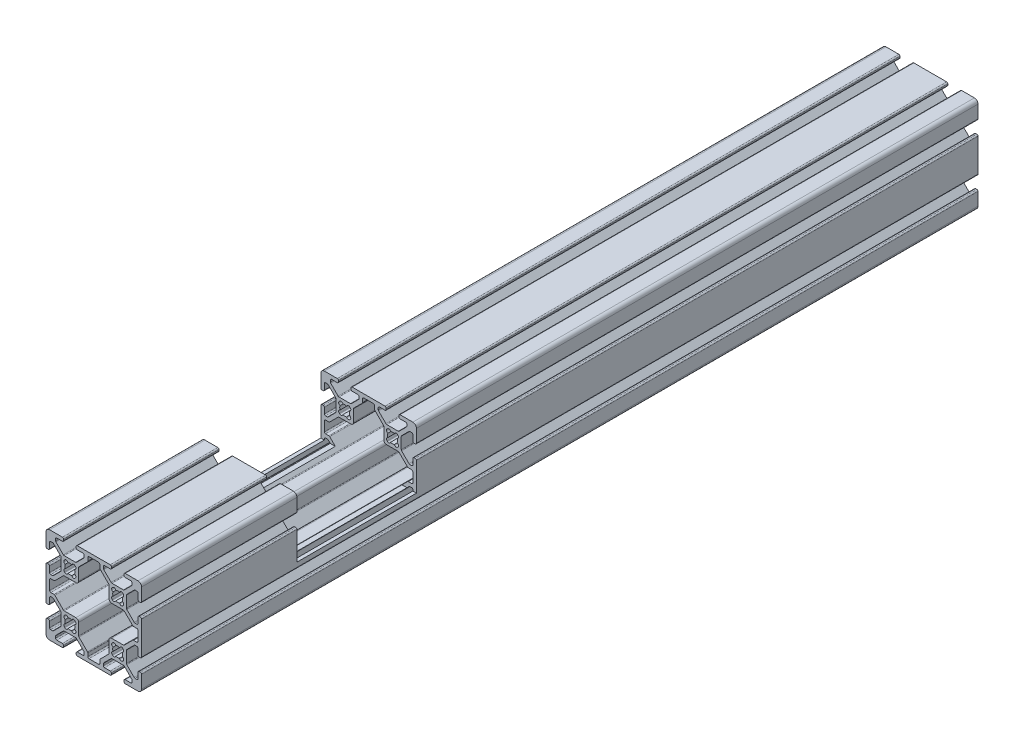
SolidWorks part; units mm, degrees
material "6105-T5 Aluminum"
ref_plane "Front Plane" through (0, 0, 0) normal (0, 0, 1) x (1, 0, 0)
ref_plane "Top Plane" through (0, 0, 0) normal (0, 1, 0) x (1, 0, 0)
ref_plane "Right Plane" through (0, 0, 0) normal (1, 0, 0) x (0, 0, -1)
sketch "Sketch1" plane through (0, 0, 0) normal (0, 0, 1) x (1, 0, 0)
  line L0 (-2.1249, 17.6955) -> (-2.3045, 17.8751)
  line L1 (-2.3045, 22.1249) -> (-2.1249, 22.3045)
  line L2 (2.1249, 22.3045) -> (2.3045, 22.1249)
  line L3 (2.3045, 17.8751) -> (2.1249, 17.6955)
  line L4 (-22.1249, 17.6955) -> (-22.3045, 17.8751)
  line L5 (-22.3045, 22.1249) -> (-22.1249, 22.3045)
  line L6 (-17.8751, 22.3045) -> (-17.6955, 22.1249)
  line L7 (-17.6955, 17.8751) -> (-17.8751, 17.6955)
  line L8 (-2.1249, -2.3045) -> (-2.3045, -2.1249)
  line L9 (-2.3045, 2.1249) -> (-2.1249, 2.3045)
  line L10 (2.1249, 2.3045) -> (2.3045, 2.1249)
  line L11 (2.3045, -2.1249) -> (2.1249, -2.3045)
  line L12 (-12.505, -7.992) -> (-12.505, -6.6448)
  line L13 (-12.6538, -6.2856) -> (-16.1962, -2.7431)
  line L14 (-16.345, -2.3839) -> (-16.345, 2.512)
  line L15 (-17.488, 3.655) -> (-22.3839, 3.655)
  line L16 (-22.7431, 3.8038) -> (-26.2856, 7.3462)
  line L17 (-26.6448, 7.495) -> (-27.992, 7.495)
  line L18 (-28.5, 8.003) -> (-28.5, 11.997)
  line L19 (-27.992, 12.505) -> (-26.6448, 12.505)
  line L20 (-26.2856, 12.6538) -> (-22.7431, 16.1962)
  line L21 (-22.3839, 16.345) -> (-17.488, 16.345)
  line L22 (-16.345, 17.488) -> (-16.345, 22.3839)
  line L23 (-16.1962, 22.7431) -> (-12.6538, 26.2856)
  line L24 (-12.505, 26.6448) -> (-12.505, 27.992)
  line L25 (-11.997, 28.5) -> (-8.003, 28.5)
  line L26 (-7.495, 27.992) -> (-7.495, 26.6448)
  line L27 (-7.3462, 26.2856) -> (-3.8038, 22.7431)
  line L28 (-3.655, 22.3839) -> (-3.655, 17.488)
  line L29 (-2.512, 16.345) -> (2.3839, 16.345)
  line L30 (2.7431, 16.1962) -> (6.2856, 12.6538)
  line L31 (6.6448, 12.505) -> (7.992, 12.505)
  line L32 (8.5, 11.997) -> (8.5, 8.003)
  line L33 (7.992, 7.495) -> (6.6448, 7.495)
  line L34 (6.2856, 7.3462) -> (2.7431, 3.8038)
  line L35 (2.3839, 3.655) -> (-2.512, 3.655)
  line L36 (-3.655, 2.512) -> (-3.655, -2.3839)
  line L37 (-3.8038, -2.7431) -> (-7.3462, -6.2856)
  line L38 (-7.495, -6.6448) -> (-7.495, -7.992)
  line L39 (-8.003, -8.5) -> (-11.997, -8.5)
  line L40 (-22.1249, -2.3045) -> (-22.3045, -2.1249)
  line L41 (-22.3045, 2.1249) -> (-22.1249, 2.3045)
  line L42 (-17.8751, 2.3045) -> (-17.6955, 2.1249)
  line L43 (-17.6955, -2.1249) -> (-17.8751, -2.3045)
  line L44 (-22.3839, -3.655) -> (-17.6161, -3.655)
  line L45 (-17.2569, -3.8038) -> (-14.1538, -6.9069)
  line L46 (-14.005, -7.2661) -> (-14.005, -7.992)
  line L47 (-14.513, -8.5) -> (-16.862, -8.5)
  line L48 (-17.37, -9.008) -> (-17.37, -9.492)
  line L49 (-16.862, -10) -> (-3.138, -10)
  line L50 (-2.63, -9.492) -> (-2.63, -9.008)
  line L51 (-3.138, -8.5) -> (-5.487, -8.5)
  line L52 (-5.995, -7.992) -> (-5.995, -7.2661)
  line L53 (-5.8462, -6.9069) -> (-2.7431, -3.8038)
  line L54 (-2.3839, -3.655) -> (2.3839, -3.655)
  line L55 (2.7431, -3.8038) -> (5.8462, -6.9069)
  line L56 (5.995, -7.2661) -> (5.995, -7.992)
  line L57 (5.487, -8.5) -> (3.138, -8.5)
  line L58 (2.63, -9.008) -> (2.63, -9.492)
  line L59 (3.138, -10) -> (8.5, -10)
  line L60 (10, -8.5) -> (10, -3.138)
  line L61 (9.492, -2.63) -> (9.008, -2.63)
  line L62 (8.5, -3.138) -> (8.5, -5.487)
  line L63 (7.992, -5.995) -> (7.2661, -5.995)
  line L64 (6.9069, -5.8462) -> (3.8038, -2.7431)
  line L65 (3.655, -2.3839) -> (3.655, 2.3839)
  line L66 (3.8038, 2.7431) -> (6.9069, 5.8462)
  line L67 (7.2661, 5.995) -> (7.992, 5.995)
  line L68 (8.5, 5.487) -> (8.5, 3.138)
  line L69 (9.008, 2.63) -> (9.492, 2.63)
  line L70 (10, 3.138) -> (10, 16.862)
  line L71 (9.492, 17.37) -> (9.008, 17.37)
  line L72 (8.5, 16.862) -> (8.5, 14.513)
  line L73 (7.992, 14.005) -> (7.2661, 14.005)
  line L74 (6.9069, 14.1538) -> (3.8038, 17.2569)
  line L75 (3.655, 17.6161) -> (3.655, 22.3839)
  line L76 (3.8038, 22.7431) -> (6.9069, 25.8462)
  line L77 (7.2661, 25.995) -> (7.992, 25.995)
  line L78 (8.5, 25.487) -> (8.5, 23.138)
  line L79 (9.008, 22.63) -> (9.492, 22.63)
  line L80 (10, 23.138) -> (10, 28.5)
  line L81 (8.5, 30) -> (3.138, 30)
  line L82 (2.63, 29.492) -> (2.63, 29.008)
  line L83 (3.138, 28.5) -> (5.487, 28.5)
  line L84 (5.995, 27.992) -> (5.995, 27.2661)
  line L85 (5.8462, 26.9069) -> (2.7431, 23.8038)
  line L86 (2.3839, 23.655) -> (-2.3839, 23.655)
  line L87 (-2.7431, 23.8038) -> (-5.8462, 26.9069)
  line L88 (-5.995, 27.2661) -> (-5.995, 27.992)
  line L89 (-5.487, 28.5) -> (-3.138, 28.5)
  line L90 (-2.63, 29.008) -> (-2.63, 29.492)
  line L91 (-3.138, 30) -> (-16.862, 30)
  line L92 (-17.37, 29.492) -> (-17.37, 29.008)
  line L93 (-16.862, 28.5) -> (-14.513, 28.5)
  line L94 (-14.005, 27.992) -> (-14.005, 27.2661)
  line L95 (-14.1538, 26.9069) -> (-17.2569, 23.8038)
  line L96 (-17.6161, 23.655) -> (-22.3839, 23.655)
  line L97 (-22.7431, 23.8038) -> (-25.8462, 26.9069)
  line L98 (-25.995, 27.2661) -> (-25.995, 27.992)
  line L99 (-25.487, 28.5) -> (-23.138, 28.5)
  line L100 (-22.63, 29.008) -> (-22.63, 29.492)
  line L101 (-23.138, 30) -> (-28.5, 30)
  line L102 (-30, 28.5) -> (-30, 23.138)
  line L103 (-29.492, 22.63) -> (-29.008, 22.63)
  line L104 (-28.5, 23.138) -> (-28.5, 25.487)
  line L105 (-27.992, 25.995) -> (-27.2661, 25.995)
  line L106 (-26.9069, 25.8462) -> (-23.8038, 22.7431)
  line L107 (-23.655, 22.3839) -> (-23.655, 17.6161)
  line L108 (-23.8038, 17.2569) -> (-26.9069, 14.1538)
  line L109 (-27.2661, 14.005) -> (-27.992, 14.005)
  line L110 (-28.5, 14.513) -> (-28.5, 16.862)
  line L111 (-29.008, 17.37) -> (-29.492, 17.37)
  line L112 (-30, 16.862) -> (-30, 3.138)
  line L113 (-29.492, 2.63) -> (-29.008, 2.63)
  line L114 (-28.5, 3.138) -> (-28.5, 5.487)
  line L115 (-27.992, 5.995) -> (-27.2661, 5.995)
  line L116 (-26.9069, 5.8462) -> (-23.8038, 2.7431)
  line L117 (-23.655, 2.3839) -> (-23.655, -2.3839)
  line L118 (-23.8038, -2.7431) -> (-26.9069, -5.8462)
  line L119 (-27.2661, -5.995) -> (-27.992, -5.995)
  line L120 (-28.5, -5.487) -> (-28.5, -3.138)
  line L121 (-29.008, -2.63) -> (-29.492, -2.63)
  line L122 (-30, -3.138) -> (-30, -8.5)
  line L123 (-28.5, -10) -> (-23.138, -10)
  line L124 (-22.63, -9.492) -> (-22.63, -9.008)
  line L125 (-23.138, -8.5) -> (-25.487, -8.5)
  line L126 (-25.995, -7.992) -> (-25.995, -7.2661)
  line L127 (-25.8462, -6.9069) -> (-22.7431, -3.8038)
  arc A0 (-1.9351, 19.196) -> (-2.3045, 17.8751) centre (-1.748, 18.4316) ccw
  arc A1 (-1.9351, 20.804) -> (-1.9351, 19.196) centre (0, 20) ccw
  arc A2 (-2.3045, 22.1249) -> (-1.9351, 20.804) centre (-1.748, 21.5684) ccw
  arc A3 (-0.804, 21.9351) -> (-2.1249, 22.3045) centre (-1.5684, 21.748) ccw
  arc A4 (0.804, 21.9351) -> (-0.804, 21.9351) centre (0, 20) ccw
  arc A5 (2.1249, 22.3045) -> (0.804, 21.9351) centre (1.5684, 21.748) ccw
  arc A6 (1.9351, 20.804) -> (2.3045, 22.1249) centre (1.748, 21.5684) ccw
  arc A7 (1.9351, 19.196) -> (1.9351, 20.804) centre (0, 20) ccw
  arc A8 (2.3045, 17.8751) -> (1.9351, 19.196) centre (1.748, 18.4316) ccw
  arc A9 (0.804, 18.0649) -> (2.1249, 17.6955) centre (1.5684, 18.252) ccw
  arc A10 (-0.804, 18.0649) -> (0.804, 18.0649) centre (0, 20) ccw
  arc A11 (-2.1249, 17.6955) -> (-0.804, 18.0649) centre (-1.5684, 18.252) ccw
  arc A12 (-21.9351, 19.196) -> (-22.3045, 17.8751) centre (-21.748, 18.4316) ccw
  arc A13 (-21.9351, 20.804) -> (-21.9351, 19.196) centre (-20, 20) ccw
  arc A14 (-22.3045, 22.1249) -> (-21.9351, 20.804) centre (-21.748, 21.5684) ccw
  arc A15 (-20.804, 21.9351) -> (-22.1249, 22.3045) centre (-21.5684, 21.748) ccw
  arc A16 (-19.196, 21.9351) -> (-20.804, 21.9351) centre (-20, 20) ccw
  arc A17 (-17.8751, 22.3045) -> (-19.196, 21.9351) centre (-18.4316, 21.748) ccw
  arc A18 (-18.0649, 20.804) -> (-17.6955, 22.1249) centre (-18.252, 21.5684) ccw
  arc A19 (-18.0649, 19.196) -> (-18.0649, 20.804) centre (-20, 20) ccw
  arc A20 (-17.6955, 17.8751) -> (-18.0649, 19.196) centre (-18.252, 18.4316) ccw
  arc A21 (-19.196, 18.0649) -> (-17.8751, 17.6955) centre (-18.4316, 18.252) ccw
  arc A22 (-20.804, 18.0649) -> (-19.196, 18.0649) centre (-20, 20) ccw
  arc A23 (-22.1249, 17.6955) -> (-20.804, 18.0649) centre (-21.5684, 18.252) ccw
  arc A24 (-1.9351, -0.804) -> (-2.3045, -2.1249) centre (-1.748, -1.5684) ccw
  arc A25 (-1.9351, 0.804) -> (-1.9351, -0.804) centre (0, 0) ccw
  arc A26 (-2.3045, 2.1249) -> (-1.9351, 0.804) centre (-1.748, 1.5684) ccw
  arc A27 (-0.804, 1.9351) -> (-2.1249, 2.3045) centre (-1.5684, 1.748) ccw
  arc A28 (0.804, 1.9351) -> (-0.804, 1.9351) centre (0, 0) ccw
  arc A29 (2.1249, 2.3045) -> (0.804, 1.9351) centre (1.5684, 1.748) ccw
  arc A30 (1.9351, 0.804) -> (2.3045, 2.1249) centre (1.748, 1.5684) ccw
  arc A31 (1.9351, -0.804) -> (1.9351, 0.804) centre (0, 0) ccw
  arc A32 (2.3045, -2.1249) -> (1.9351, -0.804) centre (1.748, -1.5684) ccw
  arc A33 (0.804, -1.9351) -> (2.1249, -2.3045) centre (1.5684, -1.748) ccw
  arc A34 (-0.804, -1.9351) -> (0.804, -1.9351) centre (0, 0) ccw
  arc A35 (-2.1249, -2.3045) -> (-0.804, -1.9351) centre (-1.5684, -1.748) ccw
  arc A36 (-12.505, -7.992) -> (-11.997, -8.5) centre (-11.997, -7.992) ccw
  arc A37 (-12.505, -6.6448) -> (-12.6538, -6.2856) centre (-13.013, -6.6448) ccw
  arc A38 (-16.345, -2.3839) -> (-16.1962, -2.7431) centre (-15.837, -2.3839) ccw
  arc A39 (-16.345, 2.512) -> (-17.488, 3.655) centre (-17.488, 2.512) ccw
  arc A40 (-22.7431, 3.8038) -> (-22.3839, 3.655) centre (-22.3839, 4.163) ccw
  arc A41 (-26.2856, 7.3462) -> (-26.6448, 7.495) centre (-26.6448, 6.987) ccw
  arc A42 (-28.5, 8.003) -> (-27.992, 7.495) centre (-27.992, 8.003) ccw
  arc A43 (-27.992, 12.505) -> (-28.5, 11.997) centre (-27.992, 11.997) ccw
  arc A44 (-26.6448, 12.505) -> (-26.2856, 12.6538) centre (-26.6448, 13.013) ccw
  arc A45 (-22.3839, 16.345) -> (-22.7431, 16.1962) centre (-22.3839, 15.837) ccw
  arc A46 (-17.488, 16.345) -> (-16.345, 17.488) centre (-17.488, 17.488) ccw
  arc A47 (-16.1962, 22.7431) -> (-16.345, 22.3839) centre (-15.837, 22.3839) ccw
  arc A48 (-12.6538, 26.2856) -> (-12.505, 26.6448) centre (-13.013, 26.6448) ccw
  arc A49 (-11.997, 28.5) -> (-12.505, 27.992) centre (-11.997, 27.992) ccw
  arc A50 (-7.495, 27.992) -> (-8.003, 28.5) centre (-8.003, 27.992) ccw
  arc A51 (-7.495, 26.6448) -> (-7.3462, 26.2856) centre (-6.987, 26.6448) ccw
  arc A52 (-3.655, 22.3839) -> (-3.8038, 22.7431) centre (-4.163, 22.3839) ccw
  arc A53 (-3.655, 17.488) -> (-2.512, 16.345) centre (-2.512, 17.488) ccw
  arc A54 (2.7431, 16.1962) -> (2.3839, 16.345) centre (2.3839, 15.837) ccw
  arc A55 (6.2856, 12.6538) -> (6.6448, 12.505) centre (6.6448, 13.013) ccw
  arc A56 (8.5, 11.997) -> (7.992, 12.505) centre (7.992, 11.997) ccw
  arc A57 (7.992, 7.495) -> (8.5, 8.003) centre (7.992, 8.003) ccw
  arc A58 (6.6448, 7.495) -> (6.2856, 7.3462) centre (6.6448, 6.987) ccw
  arc A59 (2.3839, 3.655) -> (2.7431, 3.8038) centre (2.3839, 4.163) ccw
  arc A60 (-2.512, 3.655) -> (-3.655, 2.512) centre (-2.512, 2.512) ccw
  arc A61 (-3.8038, -2.7431) -> (-3.655, -2.3839) centre (-4.163, -2.3839) ccw
  arc A62 (-7.3462, -6.2856) -> (-7.495, -6.6448) centre (-6.987, -6.6448) ccw
  arc A63 (-8.003, -8.5) -> (-7.495, -7.992) centre (-8.003, -7.992) ccw
  arc A64 (-21.9351, -0.804) -> (-22.3045, -2.1249) centre (-21.748, -1.5684) ccw
  arc A65 (-21.9351, 0.804) -> (-21.9351, -0.804) centre (-20, 0) ccw
  arc A66 (-22.3045, 2.1249) -> (-21.9351, 0.804) centre (-21.748, 1.5684) ccw
  arc A67 (-20.804, 1.9351) -> (-22.1249, 2.3045) centre (-21.5684, 1.748) ccw
  arc A68 (-19.196, 1.9351) -> (-20.804, 1.9351) centre (-20, 0) ccw
  arc A69 (-17.8751, 2.3045) -> (-19.196, 1.9351) centre (-18.4316, 1.748) ccw
  arc A70 (-18.0649, 0.804) -> (-17.6955, 2.1249) centre (-18.252, 1.5684) ccw
  arc A71 (-18.0649, -0.804) -> (-18.0649, 0.804) centre (-20, 0) ccw
  arc A72 (-17.6955, -2.1249) -> (-18.0649, -0.804) centre (-18.252, -1.5684) ccw
  arc A73 (-19.196, -1.9351) -> (-17.8751, -2.3045) centre (-18.4316, -1.748) ccw
  arc A74 (-20.804, -1.9351) -> (-19.196, -1.9351) centre (-20, 0) ccw
  arc A75 (-22.1249, -2.3045) -> (-20.804, -1.9351) centre (-21.5684, -1.748) ccw
  arc A76 (-22.3839, -3.655) -> (-22.7431, -3.8038) centre (-22.3839, -4.163) ccw
  arc A77 (-17.2569, -3.8038) -> (-17.6161, -3.655) centre (-17.6161, -4.163) ccw
  arc A78 (-14.005, -7.2661) -> (-14.1538, -6.9069) centre (-14.513, -7.2661) ccw
  arc A79 (-14.513, -8.5) -> (-14.005, -7.992) centre (-14.513, -7.992) ccw
  arc A80 (-16.862, -8.5) -> (-17.37, -9.008) centre (-16.862, -9.008) ccw
  arc A81 (-17.37, -9.492) -> (-16.862, -10) centre (-16.862, -9.492) ccw
  arc A82 (-3.138, -10) -> (-2.63, -9.492) centre (-3.138, -9.492) ccw
  arc A83 (-2.63, -9.008) -> (-3.138, -8.5) centre (-3.138, -9.008) ccw
  arc A84 (-5.995, -7.992) -> (-5.487, -8.5) centre (-5.487, -7.992) ccw
  arc A85 (-5.8462, -6.9069) -> (-5.995, -7.2661) centre (-5.487, -7.2661) ccw
  arc A86 (-2.3839, -3.655) -> (-2.7431, -3.8038) centre (-2.3839, -4.163) ccw
  arc A87 (2.7431, -3.8038) -> (2.3839, -3.655) centre (2.3839, -4.163) ccw
  arc A88 (5.995, -7.2661) -> (5.8462, -6.9069) centre (5.487, -7.2661) ccw
  arc A89 (5.487, -8.5) -> (5.995, -7.992) centre (5.487, -7.992) ccw
  arc A90 (3.138, -8.5) -> (2.63, -9.008) centre (3.138, -9.008) ccw
  arc A91 (2.63, -9.492) -> (3.138, -10) centre (3.138, -9.492) ccw
  arc A92 (8.5, -10) -> (10, -8.5) centre (8.5, -8.5) ccw
  arc A93 (10, -3.138) -> (9.492, -2.63) centre (9.492, -3.138) ccw
  arc A94 (9.008, -2.63) -> (8.5, -3.138) centre (9.008, -3.138) ccw
  arc A95 (7.992, -5.995) -> (8.5, -5.487) centre (7.992, -5.487) ccw
  arc A96 (6.9069, -5.8462) -> (7.2661, -5.995) centre (7.2661, -5.487) ccw
  arc A97 (3.655, -2.3839) -> (3.8038, -2.7431) centre (4.163, -2.3839) ccw
  arc A98 (3.8038, 2.7431) -> (3.655, 2.3839) centre (4.163, 2.3839) ccw
  arc A99 (7.2661, 5.995) -> (6.9069, 5.8462) centre (7.2661, 5.487) ccw
  arc A100 (8.5, 5.487) -> (7.992, 5.995) centre (7.992, 5.487) ccw
  arc A101 (8.5, 3.138) -> (9.008, 2.63) centre (9.008, 3.138) ccw
  arc A102 (9.492, 2.63) -> (10, 3.138) centre (9.492, 3.138) ccw
  arc A103 (10, 16.862) -> (9.492, 17.37) centre (9.492, 16.862) ccw
  arc A104 (9.008, 17.37) -> (8.5, 16.862) centre (9.008, 16.862) ccw
  arc A105 (7.992, 14.005) -> (8.5, 14.513) centre (7.992, 14.513) ccw
  arc A106 (6.9069, 14.1538) -> (7.2661, 14.005) centre (7.2661, 14.513) ccw
  arc A107 (3.655, 17.6161) -> (3.8038, 17.2569) centre (4.163, 17.6161) ccw
  arc A108 (3.8038, 22.7431) -> (3.655, 22.3839) centre (4.163, 22.3839) ccw
  arc A109 (7.2661, 25.995) -> (6.9069, 25.8462) centre (7.2661, 25.487) ccw
  arc A110 (8.5, 25.487) -> (7.992, 25.995) centre (7.992, 25.487) ccw
  arc A111 (8.5, 23.138) -> (9.008, 22.63) centre (9.008, 23.138) ccw
  arc A112 (9.492, 22.63) -> (10, 23.138) centre (9.492, 23.138) ccw
  arc A113 (10, 28.5) -> (8.5, 30) centre (8.5, 28.5) ccw
  arc A114 (3.138, 30) -> (2.63, 29.492) centre (3.138, 29.492) ccw
  arc A115 (2.63, 29.008) -> (3.138, 28.5) centre (3.138, 29.008) ccw
  arc A116 (5.995, 27.992) -> (5.487, 28.5) centre (5.487, 27.992) ccw
  arc A117 (5.8462, 26.9069) -> (5.995, 27.2661) centre (5.487, 27.2661) ccw
  arc A118 (2.3839, 23.655) -> (2.7431, 23.8038) centre (2.3839, 24.163) ccw
  arc A119 (-2.7431, 23.8038) -> (-2.3839, 23.655) centre (-2.3839, 24.163) ccw
  arc A120 (-5.995, 27.2661) -> (-5.8462, 26.9069) centre (-5.487, 27.2661) ccw
  arc A121 (-5.487, 28.5) -> (-5.995, 27.992) centre (-5.487, 27.992) ccw
  arc A122 (-3.138, 28.5) -> (-2.63, 29.008) centre (-3.138, 29.008) ccw
  arc A123 (-2.63, 29.492) -> (-3.138, 30) centre (-3.138, 29.492) ccw
  arc A124 (-16.862, 30) -> (-17.37, 29.492) centre (-16.862, 29.492) ccw
  arc A125 (-17.37, 29.008) -> (-16.862, 28.5) centre (-16.862, 29.008) ccw
  arc A126 (-14.005, 27.992) -> (-14.513, 28.5) centre (-14.513, 27.992) ccw
  arc A127 (-14.1538, 26.9069) -> (-14.005, 27.2661) centre (-14.513, 27.2661) ccw
  arc A128 (-17.6161, 23.655) -> (-17.2569, 23.8038) centre (-17.6161, 24.163) ccw
  arc A129 (-22.7431, 23.8038) -> (-22.3839, 23.655) centre (-22.3839, 24.163) ccw
  arc A130 (-25.995, 27.2661) -> (-25.8462, 26.9069) centre (-25.487, 27.2661) ccw
  arc A131 (-25.487, 28.5) -> (-25.995, 27.992) centre (-25.487, 27.992) ccw
  arc A132 (-23.138, 28.5) -> (-22.63, 29.008) centre (-23.138, 29.008) ccw
  arc A133 (-22.63, 29.492) -> (-23.138, 30) centre (-23.138, 29.492) ccw
  arc A134 (-28.5, 30) -> (-30, 28.5) centre (-28.5, 28.5) ccw
  arc A135 (-30, 23.138) -> (-29.492, 22.63) centre (-29.492, 23.138) ccw
  arc A136 (-29.008, 22.63) -> (-28.5, 23.138) centre (-29.008, 23.138) ccw
  arc A137 (-27.992, 25.995) -> (-28.5, 25.487) centre (-27.992, 25.487) ccw
  arc A138 (-26.9069, 25.8462) -> (-27.2661, 25.995) centre (-27.2661, 25.487) ccw
  arc A139 (-23.655, 22.3839) -> (-23.8038, 22.7431) centre (-24.163, 22.3839) ccw
  arc A140 (-23.8038, 17.2569) -> (-23.655, 17.6161) centre (-24.163, 17.6161) ccw
  arc A141 (-27.2661, 14.005) -> (-26.9069, 14.1538) centre (-27.2661, 14.513) ccw
  arc A142 (-28.5, 14.513) -> (-27.992, 14.005) centre (-27.992, 14.513) ccw
  arc A143 (-28.5, 16.862) -> (-29.008, 17.37) centre (-29.008, 16.862) ccw
  arc A144 (-29.492, 17.37) -> (-30, 16.862) centre (-29.492, 16.862) ccw
  arc A145 (-30, 3.138) -> (-29.492, 2.63) centre (-29.492, 3.138) ccw
  arc A146 (-29.008, 2.63) -> (-28.5, 3.138) centre (-29.008, 3.138) ccw
  arc A147 (-27.992, 5.995) -> (-28.5, 5.487) centre (-27.992, 5.487) ccw
  arc A148 (-26.9069, 5.8462) -> (-27.2661, 5.995) centre (-27.2661, 5.487) ccw
  arc A149 (-23.655, 2.3839) -> (-23.8038, 2.7431) centre (-24.163, 2.3839) ccw
  arc A150 (-23.8038, -2.7431) -> (-23.655, -2.3839) centre (-24.163, -2.3839) ccw
  arc A151 (-27.2661, -5.995) -> (-26.9069, -5.8462) centre (-27.2661, -5.487) ccw
  arc A152 (-28.5, -5.487) -> (-27.992, -5.995) centre (-27.992, -5.487) ccw
  arc A153 (-28.5, -3.138) -> (-29.008, -2.63) centre (-29.008, -3.138) ccw
  arc A154 (-29.492, -2.63) -> (-30, -3.138) centre (-29.492, -3.138) ccw
  arc A155 (-30, -8.5) -> (-28.5, -10) centre (-28.5, -8.5) ccw
  arc A156 (-23.138, -10) -> (-22.63, -9.492) centre (-23.138, -9.492) ccw
  arc A157 (-22.63, -9.008) -> (-23.138, -8.5) centre (-23.138, -9.008) ccw
  arc A158 (-25.995, -7.992) -> (-25.487, -8.5) centre (-25.487, -7.992) ccw
  arc A159 (-25.8462, -6.9069) -> (-25.995, -7.2661) centre (-25.487, -7.2661) ccw
extrude "Extrude1" add sketch "Sketch1" against normal blind 350
sketch "Sketch2" plane through (10, 0, 0) normal (1, 0, 0) x (0, 0, -1)
  line L0 (350, 30) -> (0, 30) construction
  line L1 (65, 5) -> (115, 5)
  line L2 (65, 5) -> (65, 30)
  line L3 (65, 30) -> (115, 30)
  line L4 (115, 5) -> (115, 30)
  line L5 (0, 3.138) -> (0, 16.862) construction
  dimension "D1" = 50
  dimension "D2" = 25
  dimension "D3" = 65
extrude "Cut-Extrude2" cut sketch "Sketch2" against normal blind 62
